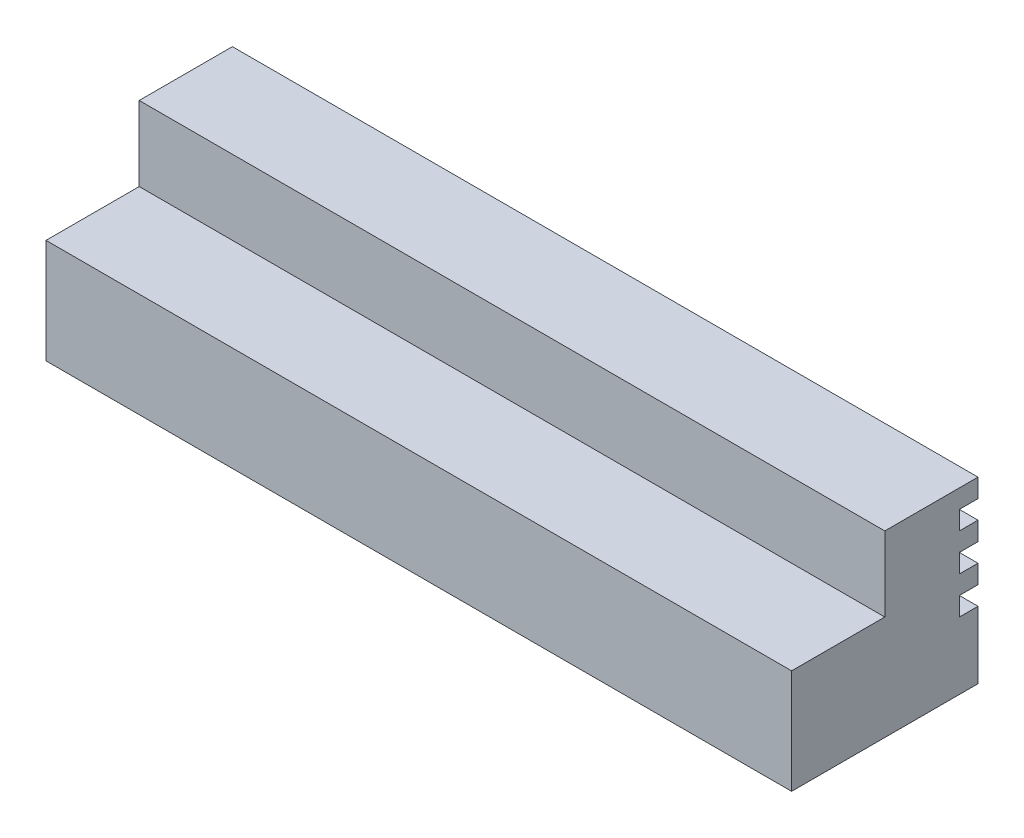
SolidWorks part; units mm, degrees
ref_plane "Plan de face" through (0, 0, 0) normal (0, 0, 1) x (1, 0, 0)
ref_plane "Plan de dessus" through (0, 0, 0) normal (0, 1, 0) x (1, 0, 0)
ref_plane "Plan de droite" through (0, 0, 0) normal (1, 0, 0) x (0, 0, -1)
sketch "Sketch1" plane through (0, 0, 0) normal (0, 1, 0) x (1, 0, 0)
  line L1 (0, 0) -> (200, 0)
  line L2 (0, 0) -> (0, 50)
  line L3 (0, 50) -> (200, 50)
  line L4 (200, 0) -> (200, 50)
  dimension "D1" = 50
  dimension "D2" = 200
extrude "Extrude1" add sketch "Sketch1" along normal blind 48
sketch "Esquisse1" plane through (200, 0, 0) normal (1, 0, 0) x (0, 0, -1)
  line L0 (50, 48) -> (50, 0) construction
  line L1 (0, 48) -> (25, 48)
  line L2 (0, 48) -> (0, 28)
  line L3 (0, 28) -> (25, 28)
  line L4 (25, 48) -> (25, 28)
  line L6 (0, 48) -> (50, 48) construction
  line L7 (50, 43) -> (45, 43)
  line L8 (50, 43) -> (50, 38)
  line L9 (50, 38) -> (45, 38)
  line L10 (45, 43) -> (45, 38)
  line L11 (50, 33) -> (45, 33)
  line L12 (50, 33) -> (50, 28)
  line L13 (50, 28) -> (45, 28)
  line L14 (45, 33) -> (45, 28)
  line L15 (50, 23) -> (45, 23)
  line L16 (50, 23) -> (50, 18)
  line L17 (50, 18) -> (45, 18)
  line L18 (45, 23) -> (45, 18)
  dimension "D1" = 25
  dimension "D2" = 20
  dimension "D3" = 5
  dimension "D4" = 5
  dimension "D5" = 5
  dimension "D6" = 5
extrude "Enlèv. mat.-Extru.1" cut sketch "Esquisse1" against normal through all
